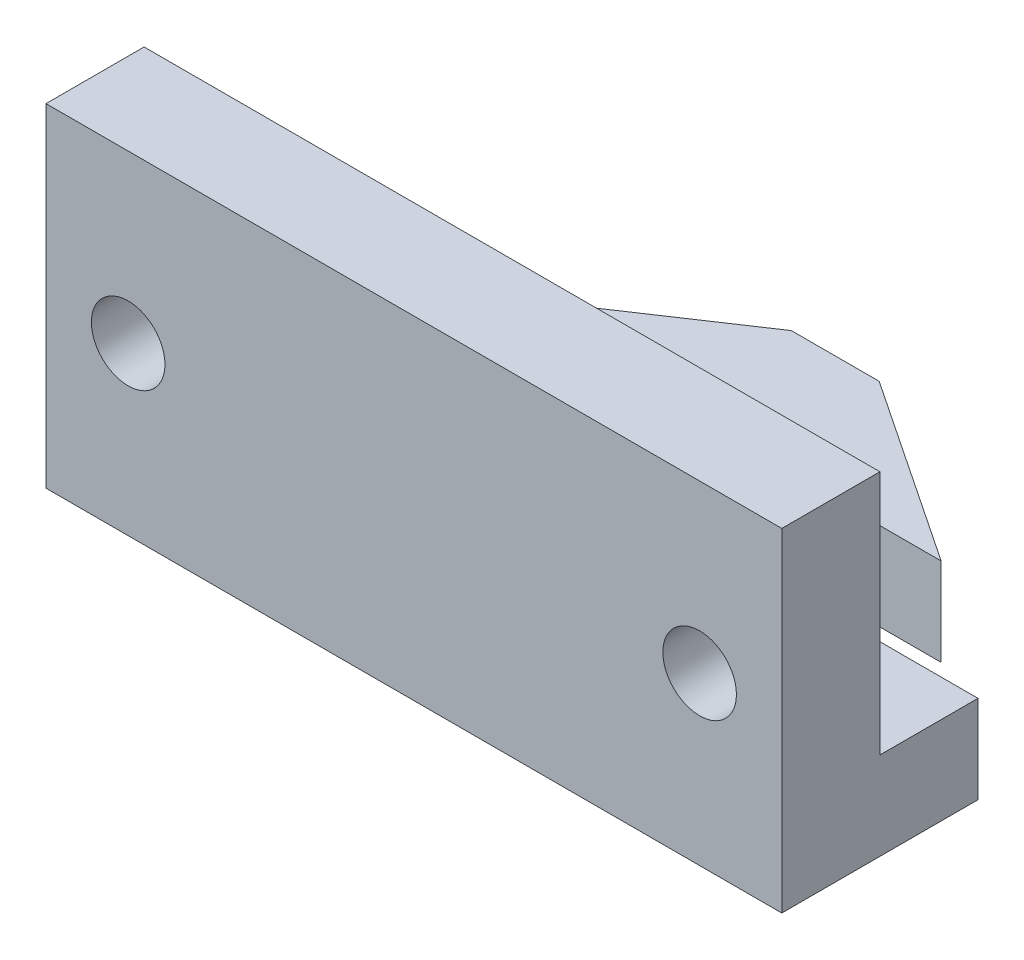
SolidWorks part; units mm, degrees
ref_plane "Front" through (0, 0, 0) normal (0, 0, 1) x (1, 0, 0)
ref_plane "Top" through (0, 0, 0) normal (0, 1, 0) x (1, 0, 0)
ref_plane "Right" through (0, 0, 0) normal (1, 0, 0) x (0, 0, -1)
sketch "Sketch1" plane through (0, 0, 0) normal (0, 1, 0) x (1, 0, 0)
  line L0 (-1.7907, 2.05) -> (-9.398, 2.05)
  line L2 (-1.7907, -2.05) -> (-1.7907, 2.05)
  line L4 (1.7907, -2.05) -> (1.7907, 2.05)
  line L7 (-9.398, 2.05) -> (-1.7907, 7.13)
  line L8 (-1.7907, 7.13) -> (1.7907, 7.13)
  line L9 (1.7907, 7.13) -> (9.398, 2.05)
  line L10 (9.398, 2.05) -> (1.7907, 2.05)
  line L11 (1.7907, -2.05) -> (15, -2.05)
  line L12 (-1.7907, -2.05) -> (-15, -2.05)
  line L13 (-15, -2.05) -> (-15, -10.05)
  line L14 (-15, -10.05) -> (15, -10.05)
  line L15 (15, -10.05) -> (15, -2.05)
  line L16 (15, -2.05) -> (1.7907, -2.05)
  point P0 (0, 0)
  point P17 (0, 7.13)
  point P19 (0, -10.05)
  point P24 (1.7907, 0)
  dimension "D1" = 18.796
  dimension "D2" = 3.5814
  dimension "D3" = 30
  dimension "D4" = 8
  dimension "D5" = 5.08
  dimension "D7" = 4.1
extrude "Boss-Extrude1" add sketch "Sketch1" along normal blind 3.5814 contours L14 L15 L11 L4 L10 L9 L8 L7 L0 L2 L12 L13
sketch "Sketch2" plane through (0, 3.5814, 0) normal (0, 1, 0) x (1, 0, 0)
  line L0 (15, -10.05) -> (15, -2.05) construction
  line L1 (-15, -10.05) -> (15, -10.05)
  line L2 (-15, -10.05) -> (-15, -6.05)
  line L3 (-15, -6.05) -> (15, -6.05)
  line L4 (15, -10.05) -> (15, -6.05)
  dimension "D1" = 4
extrude "Boss-Extrude2" add sketch "Sketch2" along normal blind 10
sketch "Sketch3" plane through (0, 0, 10.05) normal (0, 0, 1) x (1, 0, 0)
  line L0 (-15, 13.5814) -> (-15, 0) construction
  line L1 (-11.65, 6.7907) -> (11.65, 6.7907) construction
  circle A0 centre (-11.65, 6.7907) radius 1.5
  circle A1 centre (11.65, 6.7907) radius 1.5
  point P4 (0, 6.7907)
  point P7 (-15, 6.7907)
  dimension "D1" = 3
  dimension "D2" = 23.3
extrude "Cut-Extrude1" cut sketch "Sketch3" against normal up to vertex (10.05 mm away) up to point (0, 0, 0)
